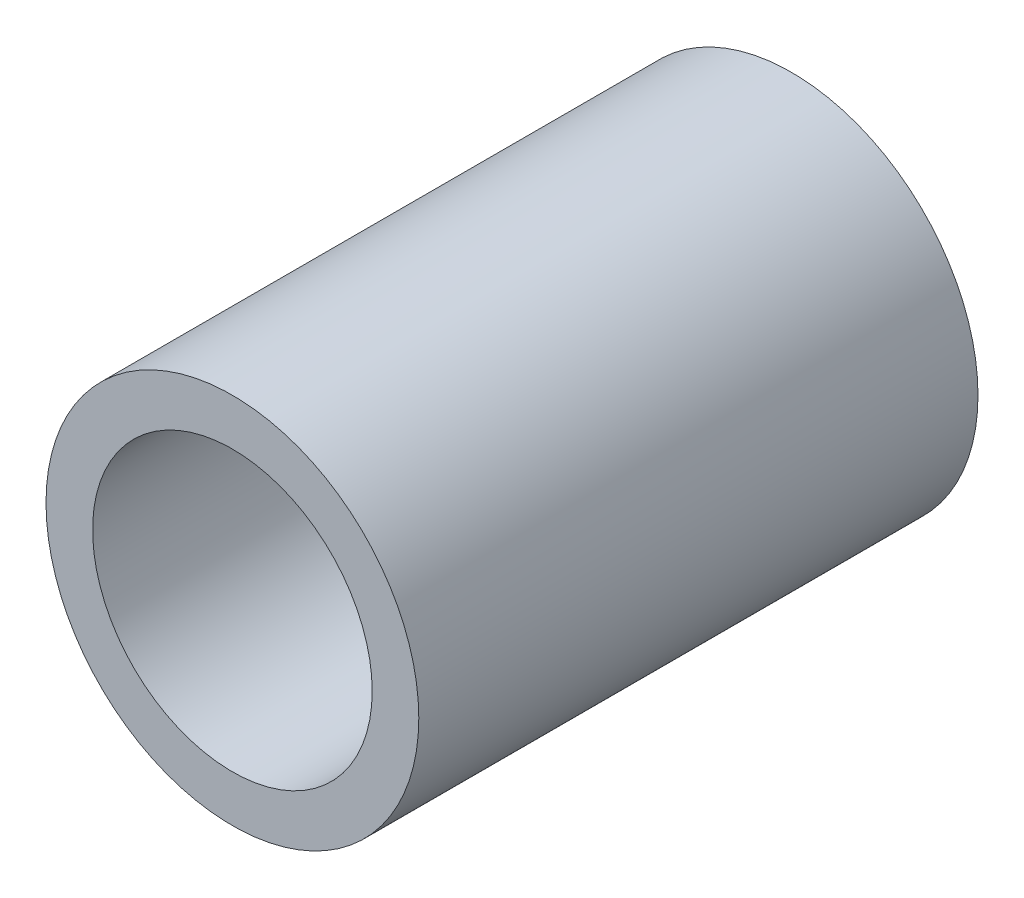
SolidWorks part; units mm, degrees
material "AISI 1020"
ref_plane "Ön Düzlem" through (0, 0, 0) normal (0, 0, 1) x (1, 0, 0)
ref_plane "Üst Düzlem" through (0, 0, 0) normal (0, 1, 0) x (1, 0, 0)
ref_plane "Sağ Düzlem" through (0, 0, 0) normal (1, 0, 0) x (0, 0, -1)
sketch "Çizim1" plane through (0, 0, 0) normal (0, 0, 1) x (1, 0, 0)
  circle A0 centre (0, 0) radius 40
  circle A1 centre (0, 0) radius 30
  dimension "D1" = 60
  dimension "D2" = 80
extrude "Yükseklik-Ekstrüzyon1" add sketch "Çizim1" along normal blind 120
